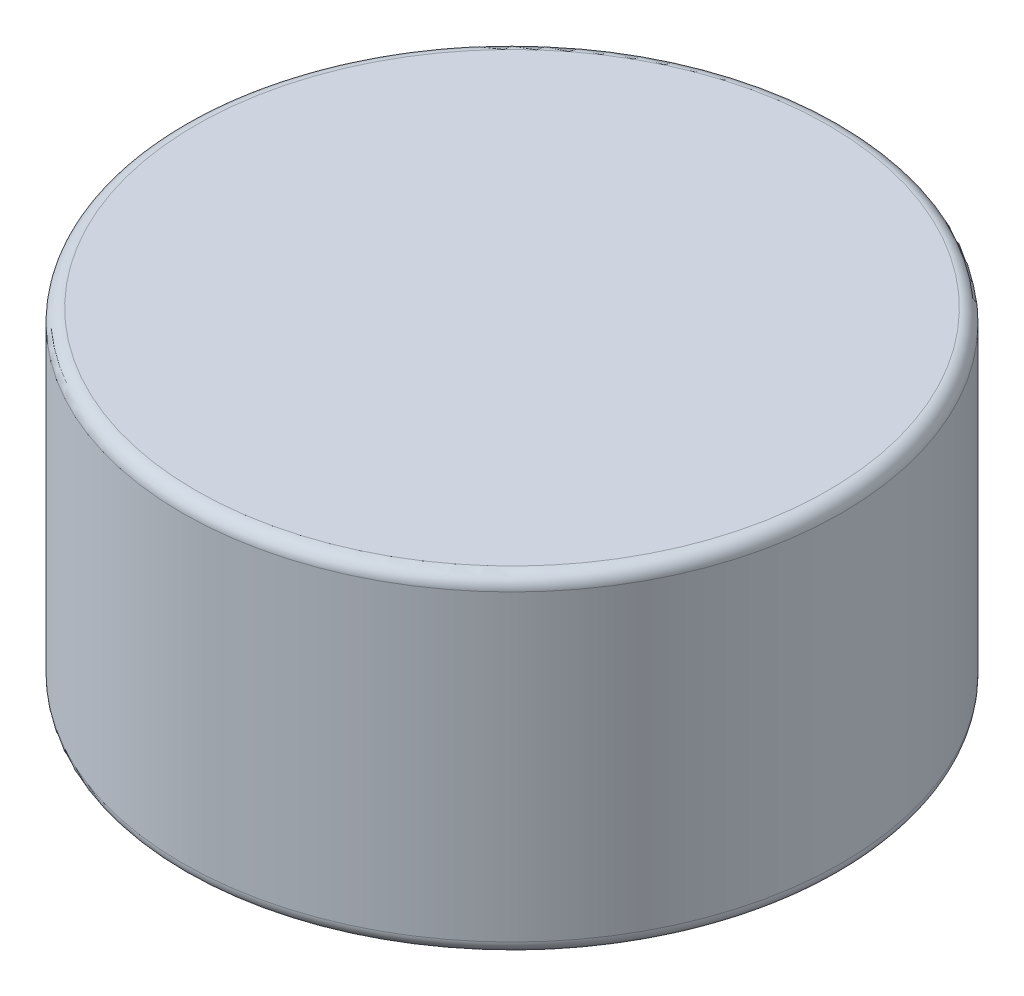
SolidWorks part; units mm, degrees
ref_plane "Front Plane" through (0, 0, 0) normal (0, 0, 1) x (1, 0, 0)
ref_plane "Top Plane" through (0, 0, 0) normal (0, 1, 0) x (1, 0, 0)
ref_plane "Right Plane" through (0, 0, 0) normal (1, 0, 0) x (0, 0, -1)
sketch "Sketch1" plane through (0, 0, 0) normal (0, 1, 0) x (1, 0, 0)
  circle A0 centre (0, 0) radius 3.175
  dimension "OD" = 6.35
extrude "Boss-Extrude1" add sketch "Sketch1" along normal mid plane 3.175
fillet "Fillet1" radius 0.127 2 edges at (0, -1.5875, 3.175) (0, 1.5875, 3.175)
equation "\"D1@Fillet1\"=\"Thickness@Boss-Extrude1\"/25"
